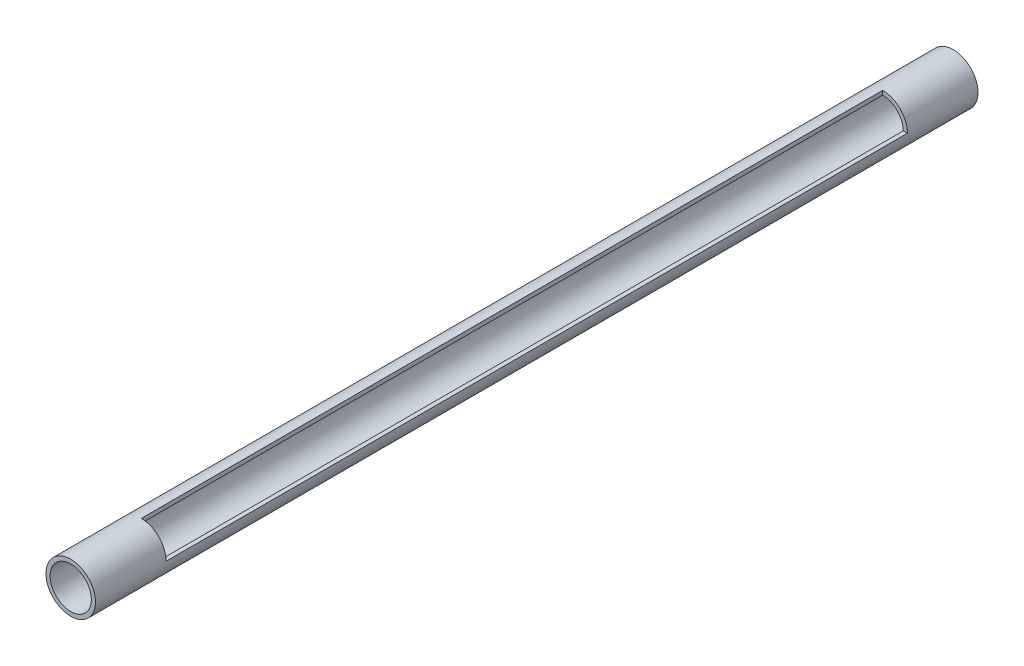
SolidWorks part; units mm, degrees
material "Rostfreier Stahl (ferritisch)"
ref_plane "Normal Z (Oben)" through (0, 0, 0) normal (0, 0, 1) x (1, 0, 0)
ref_plane "Normal Y" through (0, 0, 0) normal (0, 1, 0) x (1, 0, 0)
ref_plane "Normal X" through (0, 0, 0) normal (1, 0, 0) x (0, 0, -1)
sketch "Skizze1" plane through (0, 0, 0) normal (0, 0, 1) x (1, 0, 0)
  circle A0 centre (0, 0) radius 17.525
  circle A1 centre (0, 0) radius 21.035
  dimension "D1" = 42.07
  dimension "D2" = 35.05
extrude "Aufsatz-Linear austragen1" add sketch "Skizze1" along normal mid plane 750
thread "Gewinde1" pitch 2.1167 start angle 0, offset 0, length 15.24, pitch 2.1167, diameter 42.07
ref_plane "Ebene3" through (-21.035, 0, 375) normal (0, -1, 0) x (-0.9998, 0, -0.0175)
sketch "Gewindeprofil3" plane through (-21.035, 0, 375) normal (0, -1, 0) x (-0.9998, 0, -0.0175)
  line L0 (0, 0) -> (0, 2.1167) construction
  line L1 (0, 0) -> (1.1457, 0.6615)
  line L2 (1.1457, 0.6615) -> (1.1457, 0.926)
  line L3 (1.1457, 0.926) -> (0, 1.5875)
  line L4 (1.1457, 0.7937) -> (0, 0.7937) construction
  line L11 (0, 0) -> (0, 1.5875)
  point P2 (0, 0)
  dimension "Pitch" = 2.1167
  dimension "Profile_Angle" = 60
  dimension "Profile_Land" = 0.2646
  dimension "Profile_Height" = 1.1457
thread "Gewinde2" pitch 2.1167 start angle 0, offset 0, length 15.24, pitch 2.1167, diameter 42.07
ref_plane "Ebene4" through (21.035, 0, -375) normal (0, -1, 0) x (0.9998, 0, 0.0175)
sketch "Gewindeprofil4" plane through (21.035, 0, -375) normal (0, -1, 0) x (0.9998, 0, 0.0175)
  line L0 (0, 0) -> (0, 2.1167) construction
  line L1 (0, 0) -> (1.1457, 0.6615)
  line L2 (1.1457, 0.6615) -> (1.1457, 0.926)
  line L3 (1.1457, 0.926) -> (0, 1.5875)
  line L4 (1.1457, 0.7937) -> (0, 0.7937) construction
  line L11 (0, 0) -> (0, 1.5875)
  point P2 (0, 0)
  dimension "Pitch" = 2.1167
  dimension "Profile_Angle" = 60
  dimension "Profile_Land" = 0.2646
  dimension "Profile_Height" = 1.1457
sketch "Skizze2" plane through (0, 0, 0) normal (0, 1, 0) x (1, 0, 0)
  line L5 (0, 0) -> (50, 0)
  line L9 (0, 315) -> (50, 315)
  line L10 (0, 315) -> (0, -315)
  line L11 (0, -315) -> (50, -315)
  line L12 (50, 315) -> (50, -315)
  line L13 (21.035, -375) -> (21.035, 375) construction
  line L15 (0, 375) -> (0, -375) construction
  line L16 (17.525, 375) -> (-17.525, 375) construction
  line L17 (-21.035, -375) -> (21.035, -375) construction
  dimension "D1" = 50
  dimension "D2" = 60
extrude "Schnitt-Linear austragen1" cut sketch "Skizze2" along normal through all contours L12 L11 L10 L9
